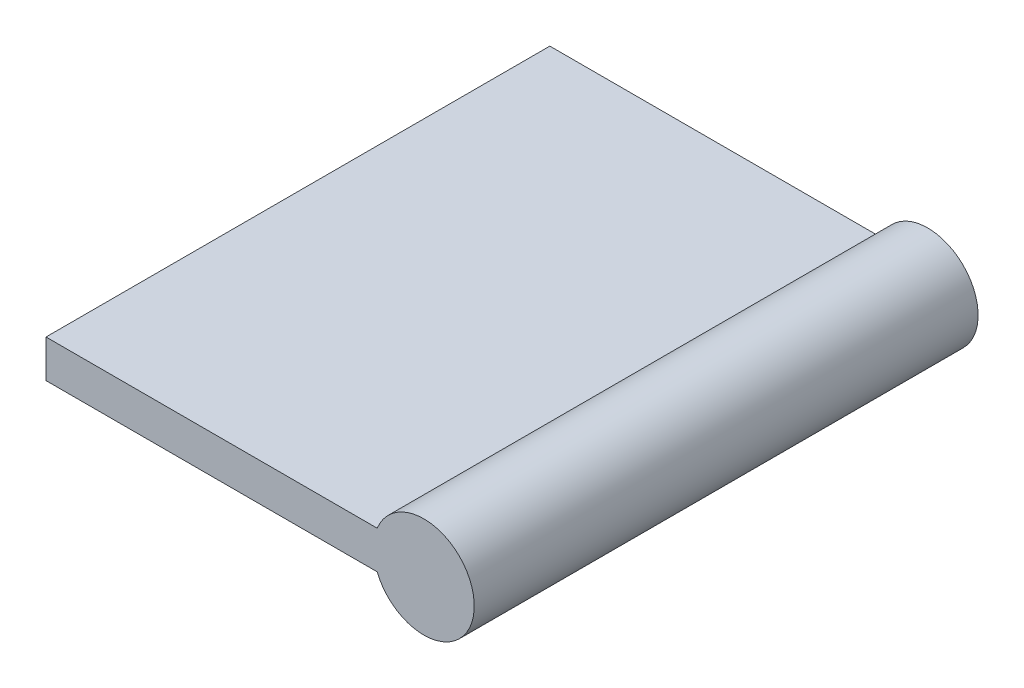
SolidWorks part; units mm, degrees
ref_plane "Front Plane" through (0, 0, 0) normal (0, 0, 1) x (1, 0, 0)
ref_plane "Top Plane" through (0, 0, 0) normal (0, 1, 0) x (1, 0, 0)
ref_plane "Right Plane" through (0, 0, 0) normal (1, 0, 0) x (0, 0, -1)
sketch "Sketch1" plane through (0, 0, 0) normal (0, 0, 1) x (1, 0, 0)
  circle A0 centre (0, 0) radius 2
  dimension "D1" = 4
extrude "Boss-Extrude1" add sketch "Sketch1" along normal mid plane 20
sketch "Sketch2" plane through (0, 0, 0) normal (1, 0, 0) x (0, 0, -1)
  line L0 (-10, 2) -> (-10, -2) construction
  line L1 (10, 0.75) -> (-10, 0.75)
  line L2 (10, 0.75) -> (10, -0.75)
  line L3 (10, -0.75) -> (-10, -0.75)
  line L4 (-10, 0.75) -> (-10, -0.75)
  line L5 (10, 0.75) -> (-10, -0.75) construction
  line L6 (10, -0.75) -> (-10, 0.75) construction
  point P0 (0, 0)
  dimension "D1" = 1.5
extrude "Boss-Extrude2" add sketch "Sketch2" against normal blind 15
